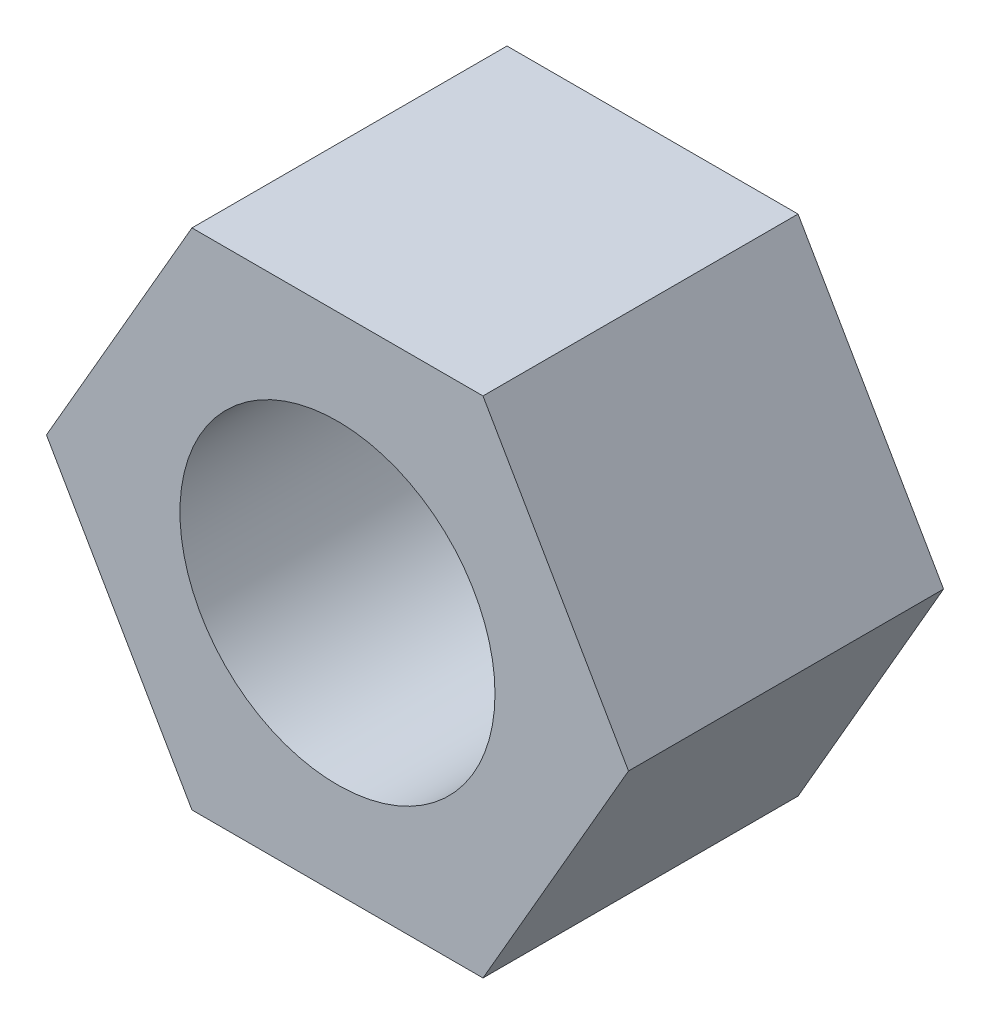
SolidWorks part; units mm, degrees
ref_plane "前视基准面" through (0, 0, 0) normal (0, 0, 1) x (1, 0, 0)
ref_plane "上视基准面" through (0, 0, 0) normal (0, 1, 0) x (1, 0, 0)
ref_plane "右视基准面" through (0, 0, 0) normal (1, 0, 0) x (0, 0, -1)
other "Configuration Table"
sketch "草图1" plane through (0, 0, 0) normal (0, 0, 1) x (1, 0, 0)
  line L0 (4.6188, 0) -> (2.3094, 4)
  line L1 (2.3094, 4) -> (-2.3094, 4)
  line L2 (-2.3094, 4) -> (-4.6188, 0)
  line L3 (-4.6188, 0) -> (-2.3094, -4)
  line L4 (-2.3094, -4) -> (2.3094, -4)
  line L5 (2.3094, -4) -> (4.6188, 0)
  circle A0 centre (0, 0) radius 2.5
extrude "凸台-拉伸1" add sketch "草图1" against normal blind 5
